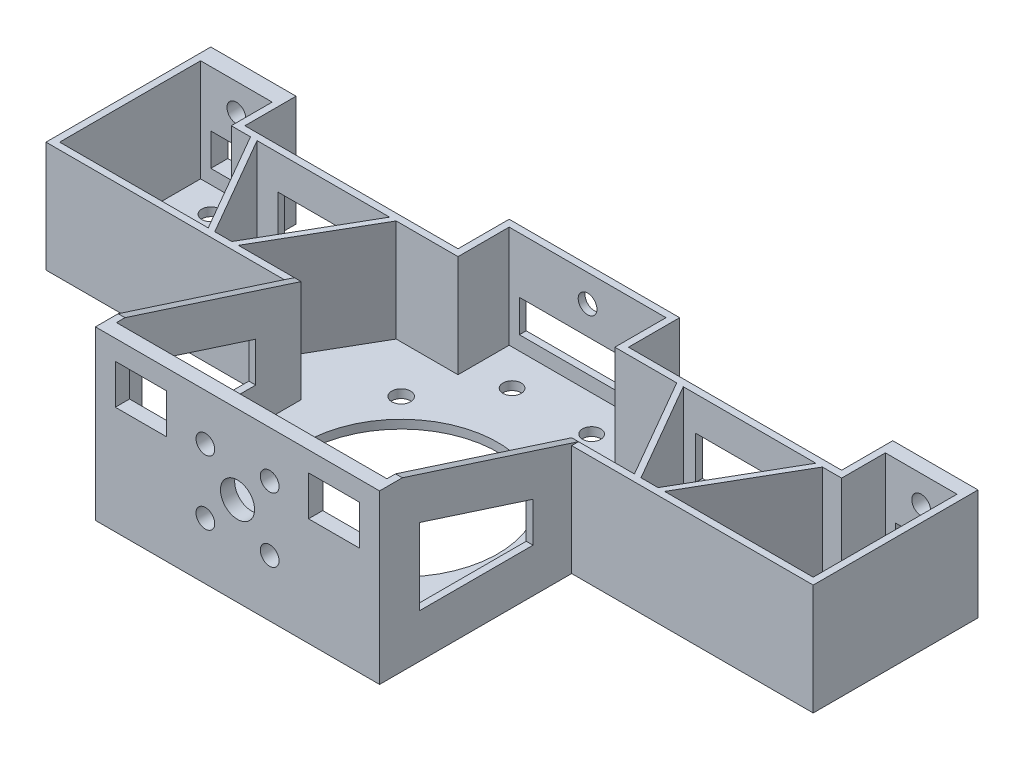
SolidWorks part; units mm, degrees
ref_plane "前视基准面" through (0, 0, 0) normal (0, 0, 1) x (1, 0, 0)
ref_plane "上视基准面" through (0, 0, 0) normal (0, 1, 0) x (1, 0, 0)
ref_plane "右视基准面" through (0, 0, 0) normal (1, 0, 0) x (0, 0, -1)
sketch "草图2" plane through (0, 0, 0) normal (0, 1, 0) x (1, 0, 0)
  line L15 (-42.5, 33.8) -> (-42.5, 62.8)
  line L16 (-42.5, 62.8) -> (-27.5, 62.8)
  line L17 (-27.5, 62.8) -> (-27.5, 53.8)
  line L18 (-27.5, 53.8) -> (10, 53.8)
  line L19 (10, 53.8) -> (10, 62.8)
  line L20 (10, 62.8) -> (40, 62.8)
  line L21 (40, 62.8) -> (40, 53.8)
  line L22 (40, 53.8) -> (77.5, 53.8)
  line L23 (77.5, 53.8) -> (77.5, 62.8)
  line L24 (77.5, 62.8) -> (92.5, 62.8)
  line L25 (92.5, 62.8) -> (92.5, 33.8)
  line L27 (-42.5, 33.8) -> (0, 33.8)
  line L28 (0, 33.8) -> (0, 0)
  line L29 (0, 0) -> (50, 0)
  line L30 (50, 0) -> (50, 33.8)
  line L31 (50, 33.8) -> (92.5, 33.8)
  line L32 (25, -43.9837) -> (25, 74.5213) construction
  line L33 (85, 58.3) -> (85, -14.8283) construction
  line L34 (-35, 58.3) -> (-35, -33.736) construction
  circle A1 centre (-35, 55.3122) radius 1.6
  circle A3 centre (85, 55.3122) radius 1.6
  circle A6 centre (18, 55.3122) radius 1.6
  circle A7 centre (32, 55.3122) radius 1.6
  circle A10 centre (25, 28.8) radius 17
  circle A11 centre (40.5, 44.3) radius 1.65
  circle A12 centre (40.5, 13.3) radius 1.65
  circle A13 centre (9.5, 13.3) radius 1.65
  circle A14 centre (9.5, 44.3) radius 1.65
  point P0 (-35, 55.3122)
  point P1 (85, 55.3122)
  point P2 (85, 58.3)
  point P3 (-35, 58.3)
  point P6 (18, 55.3122)
  point P50 (25, 28.8)
  dimension "D2" = 120
  dimension "D20" = 3.2
  dimension "D22" = 34
  dimension "D7" = 28.8
  dimension "D10" = 50
  dimension "D11" = 25
  dimension "D14" = 3.3
  dimension "D17" = 31
  dimension "D4" = 14
  dimension "D6" = 25
  dimension "D9" = 30
  dimension "D12" = 15
  dimension "D13" = 15
  dimension "D15" = 20
  dimension "D16" = 4
  dimension "D18" = 4.5
  dimension "D19" = 25
extrude "凸台-拉伸2" add sketch "草图2" along normal blind 1.5
sketch "草图6" plane through (0, 1.5, 0) normal (0, 1, 0) x (1, 0, 0)
  line L9 (25, 28.8) -> (25, -10.253) construction
  line L12 (10, 53.8) -> (-27.5, 53.8) construction
  line L13 (10, 62.8) -> (10, 53.8) construction
  line L14 (40, 62.8) -> (10, 62.8) construction
  line L15 (40, 53.8) -> (40, 62.8) construction
  line L16 (77.5, 53.8) -> (40, 53.8) construction
  line L17 (77.5, 62.8) -> (77.5, 53.8) construction
  line L18 (92.5, 62.8) -> (77.5, 62.8) construction
  line L19 (92.5, 33.8) -> (92.5, 62.8) construction
  line L20 (50, 33.8) -> (92.5, 33.8) construction
  line L21 (50, 0) -> (50, 33.8) construction
  line L22 (0, 0) -> (50, 0) construction
  line L23 (0, 33.8) -> (0, 0) construction
  line L24 (-42.5, 33.8) -> (0, 33.8) construction
  line L25 (-42.5, 62.8) -> (-42.5, 33.8) construction
  line L26 (-27.5, 53.8) -> (-27.5, 62.8) construction
  line L27 (-27.5, 62.8) -> (-42.5, 62.8) construction
  line L28 (10, 53.8) -> (-27.5, 53.8)
  line L29 (10, 62.8) -> (10, 53.8)
  line L30 (40, 62.8) -> (10, 62.8)
  line L31 (40, 53.8) -> (40, 62.8)
  line L32 (77.5, 53.8) -> (40, 53.8)
  line L33 (77.5, 62.8) -> (77.5, 53.8)
  line L34 (92.5, 62.8) -> (77.5, 62.8)
  line L35 (92.5, 33.8) -> (92.5, 62.8)
  line L36 (50, 33.8) -> (92.5, 33.8)
  line L37 (50, 0) -> (50, 33.8)
  line L38 (0, 0) -> (50, 0)
  line L39 (0, 33.8) -> (0, 0)
  line L40 (-42.5, 33.8) -> (0, 33.8)
  line L41 (-42.5, 62.8) -> (-42.5, 33.8)
  line L42 (-27.5, 53.8) -> (-27.5, 62.8)
  line L43 (-27.5, 62.8) -> (-42.5, 62.8)
  line L44 (11.2, 52.6) -> (-28.7, 52.6)
  line L45 (-28.7, 52.6) -> (-28.7, 59.8)
  line L46 (-28.7, 59.8) -> (-41.3, 59.8)
  line L47 (-41.3, 59.8) -> (-41.3, 35)
  line L48 (-41.3, 35) -> (1.2, 35)
  line L49 (1.2, 35) -> (1.2, 2.5)
  line L50 (1.2, 2.5) -> (48.8, 2.5)
  line L51 (48.8, 2.5) -> (48.8, 35)
  line L52 (48.8, 35) -> (91.3, 35)
  line L53 (91.3, 35) -> (91.3, 60.3)
  line L54 (91.3, 60.3) -> (78.7, 60.3)
  line L55 (78.7, 60.3) -> (78.7, 52.6)
  line L56 (78.7, 52.6) -> (38.8, 52.6)
  line L57 (38.8, 52.6) -> (38.8, 61.6)
  line L58 (38.8, 61.6) -> (11.2, 61.6)
  line L59 (11.2, 61.6) -> (11.2, 52.6)
  dimension "D1" = 2.5
  dimension "D2" = 1.2
  dimension "D3" = 1.2
  dimension "D4" = 3
  dimension "D5" = 1.2
  dimension "D6" = 1.2
  dimension "D7" = 1.2
  dimension "D8" = 1.2
  dimension "D9" = 1.2
  dimension "D10" = 1.2
  dimension "D11" = 2.5
  dimension "D12" = 1.2
  dimension "D13" = 1.2
  dimension "D14" = 1.2
  dimension "D15" = 1.2
  dimension "D16" = 1.2
extrude "凸台-拉伸3" add sketch "草图6" along normal blind 18
sketch "草图11" plane through (0, 19.5, 0) normal (0, 1, 0) x (1, 0, 0)
  line L0 (1.2, 35) -> (1.2, 2.5)
  line L1 (1.2, 2.5) -> (48.8, 2.5)
  line L2 (48.8, 2.5) -> (48.8, 35)
  line L3 (48.8, 35) -> (50, 35)
  line L4 (48.8, 35) -> (91.3, 35) construction
  line L5 (50, 35) -> (50, 0)
  line L6 (50, 0) -> (50, 33.8) construction
  line L7 (50, 0) -> (0, 0)
  line L8 (0, 0) -> (0, 35)
  line L9 (-41.3, 35) -> (1.2, 35) construction
  line L10 (0, 35) -> (1.2, 35)
extrude "凸台-拉伸4" add sketch "草图11" along normal blind 10
sketch "草图12" plane through (0, 0, 0) normal (-1, 0, 0) x (0, 0, 1)
  line L0 (-35, 19.5) -> (-4, 29.5)
  line L1 (-35, 29.5) -> (0, 29.5) construction
  line L2 (-4, 29.5) -> (-35, 29.5)
  line L3 (-35, 29.5) -> (-35, 19.5)
  line L4 (0, 29.5) -> (0, 0) construction
  dimension "D1" = 4
extrude "切除-拉伸5" cut sketch "草图12" against normal through all
sketch "草图10" plane through (0, 0, 0) normal (0, 0, 1) x (1, 0, 0)
  line L0 (25, 37.2917) -> (25, -8.8083) construction
  line L1 (0, 29.5) -> (50, 29.5) construction
  line L2 (3.5, 26) -> (12.5, 26)
  line L3 (3.5, 26) -> (3.5, 19)
  line L4 (3.5, 19) -> (12.5, 19)
  line L5 (0, 0) -> (50, 0) construction
  line L6 (0, 29.5) -> (0, 0) construction
  line L7 (50, 29.5) -> (50, 0) construction
  line L8 (12.5, 26) -> (12.5, 19)
  line L9 (0, 29.5) -> (0, 0) construction
  line L10 (46.5, 19) -> (37.5, 19)
  line L11 (37.5, 26) -> (37.5, 19)
  line L12 (46.5, 26) -> (37.5, 26)
  line L13 (46.5, 26) -> (46.5, 19)
  circle A0 centre (25, 15.6569) radius 3
  circle A1 centre (30.6569, 21.3137) radius 1.65
  circle A2 centre (30.6569, 10) radius 1.65
  circle A3 centre (19.3431, 10) radius 1.65
  circle A4 centre (19.3431, 21.3137) radius 1.65
  point P19 (25, 15.6569)
  dimension "D1" = 10
  dimension "D2" = 6
  dimension "D3" = 3.3
  dimension "D4" = 8
  dimension "D6" = 3.5
  dimension "D7" = 3.5
  dimension "D8" = 9
  dimension "D9" = 7
  dimension "D5" = 4
extrude "切除-拉伸4" cut sketch "草图10" against normal blind 5
sketch "草图13" plane through (0, 1.5, 0) normal (0, 1, 0) x (1, 0, 0)
  line L1 (11.2, 52.6) -> (-28.7, 52.6) construction
  line L2 (-41.3, 35) -> (0, 35) construction
  line L6 (11.2, 52.6) -> (-28.7, 52.6) construction
  line L8 (-27.5, 53.8) -> (-27.5, 62.8) construction
  line L10 (-0.8386, 52.6) -> (0.3161, 52.6)
  line L13 (-12.5, 35) -> (-12.5, 56.0294) construction
  line L14 (0, 35) -> (0, 4) construction
  line L15 (25, 62.8) -> (25, -17.4304) construction
  line L16 (40, 62.8) -> (10, 62.8) construction
  line L25 (-0.8386, 52.6) -> (-11, 35)
  line L26 (-11, 35) -> (-9.8453, 35)
  line L27 (-9.8453, 35) -> (0.3161, 52.6)
  line L28 (-14, 35) -> (-15.1547, 35)
  line L29 (-24.1614, 52.6) -> (-14, 35)
  line L30 (-24.1614, 52.6) -> (-25.3161, 52.6)
  line L31 (-15.1547, 35) -> (-25.3161, 52.6)
  line L32 (61, 35) -> (59.8453, 35)
  line L33 (50.8386, 52.6) -> (61, 35)
  line L34 (50.8386, 52.6) -> (49.6839, 52.6)
  line L35 (59.8453, 35) -> (49.6839, 52.6)
  line L36 (74.1614, 52.6) -> (64, 35)
  line L37 (74.1614, 52.6) -> (75.3161, 52.6)
  line L38 (65.1547, 35) -> (75.3161, 52.6)
  line L39 (64, 35) -> (65.1547, 35)
  point P27 (0, 0)
  dimension "D1" = 1
  dimension "D2" = 60
  dimension "D3" = 15
  dimension "D4" = 12.5
  dimension "D5" = 1.5
extrude "凸台-拉伸5" add sketch "草图13" along normal up to surface (18 mm away) up to face at (25, 19.5, -51.4643)
sketch "草图14" plane through (0, 0, -62.8) normal (0, 0, -1) x (-1, 0, 0)
  line L0 (-25, 46.072) -> (-25, -18.623) construction
  line L1 (42.5, 19.5) -> (42.5, 0) construction
  line L2 (-92.5, 19.5) -> (-92.5, 0) construction
  line L3 (27.5, 0) -> (42.5, 0) construction
  circle A0 centre (35, 14.7) radius 1.65
  circle A1 centre (-85, 14.7) radius 1.65
  circle A2 centre (-25, 14.7) radius 1.65
  point P14 (0, 0)
  dimension "D1" = 3.3
  dimension "D2" = 120
  dimension "D3" = 14.7
extrude "切除-拉伸6" cut sketch "草图14" against normal blind 10
sketch "草图16" plane through (0, 0, 0) normal (-1, 0, 0) x (0, 0, 1)
  line L0 (-19, 24.6613) -> (-19, 16.5)
  line L1 (-35, 19.5) -> (-4, 29.5) construction
  line L2 (-19, 16.5) -> (-35, 16.5)
  line L3 (-35, 19.5) -> (-35, 16.5)
  line L4 (-35, 19.5) -> (-19, 24.6613)
  dimension "D1" = 16
  dimension "D2" = 3
sketch "草图17" plane through (0, 0, 0) normal (-1, 0, 0) x (0, 0, 1)
  line L0 (-7, 21.1771) -> (-27, 14.7255)
  line L5 (-27, 14.7255) -> (-27, 7.7255)
  line L12 (-27, 7.7255) -> (-7, 7.7255)
  line L15 (-7, 7.7255) -> (-7, 21.1771)
  line L16 (-35, 19.5) -> (-4, 29.5) construction
  line L17 (0, 29.5) -> (0, 0) construction
  dimension "D1" = 7
  dimension "D2" = 20
  dimension "D3" = 7
  dimension "D4" = 7
extrude "切除-拉伸7" cut sketch "草图17" against normal through all
sketch "草图18" plane through (0, 0, -62.8) normal (0, 0, -1) x (-1, 0, 0)
  line L0 (-92.5, 19.5) -> (-92.5, 0) construction
  line L1 (-89.5, 9.7) -> (-80.5, 9.7)
  line L2 (-89.5, 9.7) -> (-89.5, 4)
  line L3 (-89.5, 4) -> (-80.5, 4)
  line L4 (-80.5, 9.7) -> (-80.5, 4)
  line L5 (-37, 9.7) -> (-13, 9.7)
  line L6 (-37, 9.7) -> (-37, 4)
  line L7 (-37, 4) -> (-13, 4)
  line L8 (-13, 9.7) -> (-13, 4)
  line L9 (-77.5, 19.5) -> (-77.5, 0) construction
  line L10 (-92.5, 0) -> (-77.5, 0) construction
  line L11 (-40, 19.5) -> (-40, 0) construction
  line L12 (-10, 19.5) -> (-10, 0) construction
  line L13 (-25, 19.5) -> (-25, -20.1483) construction
  line L14 (-40, 19.5) -> (-10, 19.5) construction
  line L15 (39.5, 4) -> (30.5, 4)
  line L16 (30.5, 9.7) -> (30.5, 4)
  line L17 (39.5, 9.7) -> (30.5, 9.7)
  line L18 (39.5, 9.7) -> (39.5, 4)
  circle A0 centre (-85, 14.7) radius 1.65 construction
  dimension "D1" = 3
  dimension "D2" = 3
  dimension "D3" = 4
  dimension "D4" = 5
  dimension "D5" = 3
  dimension "D6" = 3
extrude "切除-拉伸8" cut sketch "草图18" against normal blind 10
sketch "草图20" plane through (0, 1.5, 0) normal (0, 1, 0) x (1, 0, 0)
  line L8 (-12.5, 40.4019) -> (-7.7668, 48.6)
  line L9 (-7.7668, 48.6) -> (-17.2332, 48.6)
  line L10 (-17.2332, 48.6) -> (-12.5, 40.4019)
  line L11 (-12.5, 40.4019) -> (-7.7668, 48.6)
  line L12 (-7.7668, 48.6) -> (-17.2332, 48.6)
  line L13 (-17.2332, 48.6) -> (-12.5, 40.4019)
  line L18 (62.5, 40.4019) -> (67.2332, 48.6)
  line L19 (67.2332, 48.6) -> (57.7668, 48.6)
  line L20 (57.7668, 48.6) -> (62.5, 40.4019)
  line L21 (62.5, 40.4019) -> (67.2332, 48.6)
  line L22 (67.2332, 48.6) -> (57.7668, 48.6)
  line L23 (57.7668, 48.6) -> (62.5, 40.4019)
  line L26 (-36.3, 50.374) -> (-33.7, 50.374)
  line L27 (86.3, 40) -> (73.815, 40)
  line L28 (25, 62.8) -> (25, 22.7377) construction
  line L29 (40, 62.8) -> (10, 62.8) construction
  line L30 (73.815, 40) -> (78.2028, 47.6)
  line L31 (78.2028, 47.6) -> (83.7, 47.6)
  line L32 (-23.815, 40) -> (-28.2028, 47.6)
  line L33 (-28.2028, 47.6) -> (-33.7, 47.6)
  line L34 (-33.7, 47.6) -> (-33.7, 54.8)
  line L35 (-33.7, 54.8) -> (-36.3, 54.8)
  line L36 (-36.3, 54.8) -> (-36.3, 40)
  line L37 (-36.3, 40) -> (-23.815, 40)
  line L38 (-23.815, 40) -> (-28.2028, 47.6)
  line L39 (-28.2028, 47.6) -> (-33.7, 47.6)
  line L40 (-33.7, 47.6) -> (-33.7, 50.374)
  line L42 (-36.3, 50.374) -> (-36.3, 40)
  line L43 (-36.3, 40) -> (-23.815, 40)
  line L44 (83.7, 47.6) -> (83.7, 50.374)
  line L45 (86.3, 50.374) -> (83.7, 50.374)
  line L46 (86.3, 50.374) -> (86.3, 40)
  dimension "D1" = 4
  dimension "D2" = 4
  dimension "D3" = 5
extrude "切除-拉伸9" cut sketch "草图20" against normal blind 10
sketch "草图21" plane through (0, 0, -53.8) normal (0, 0, -1) x (-1, 0, 0)
  line L0 (-10, 19.5) -> (27.5, 19.5) construction
  line L1 (3, 13.5) -> (20.5, 13.5)
  line L2 (3, 13.5) -> (3, 6)
  line L3 (3, 6) -> (20.5, 6)
  line L4 (20.5, 13.5) -> (20.5, 6)
  line L5 (-10, 19.5) -> (-10, 0) construction
  line L6 (27.5, 19.5) -> (27.5, 0) construction
  line L7 (-25, 19.5) -> (-25, -16.7535) construction
  line L8 (-40, 19.5) -> (-10, 19.5) construction
  line L9 (-53, 6) -> (-70.5, 6)
  line L10 (-70.5, 13.5) -> (-70.5, 6)
  line L11 (-53, 13.5) -> (-70.5, 13.5)
  line L12 (-53, 13.5) -> (-53, 6)
  dimension "D1" = 6
  dimension "D2" = 6
  dimension "D3" = 13
  dimension "D4" = 7
extrude "切除-拉伸10" cut sketch "草图21" against normal blind 1.2
